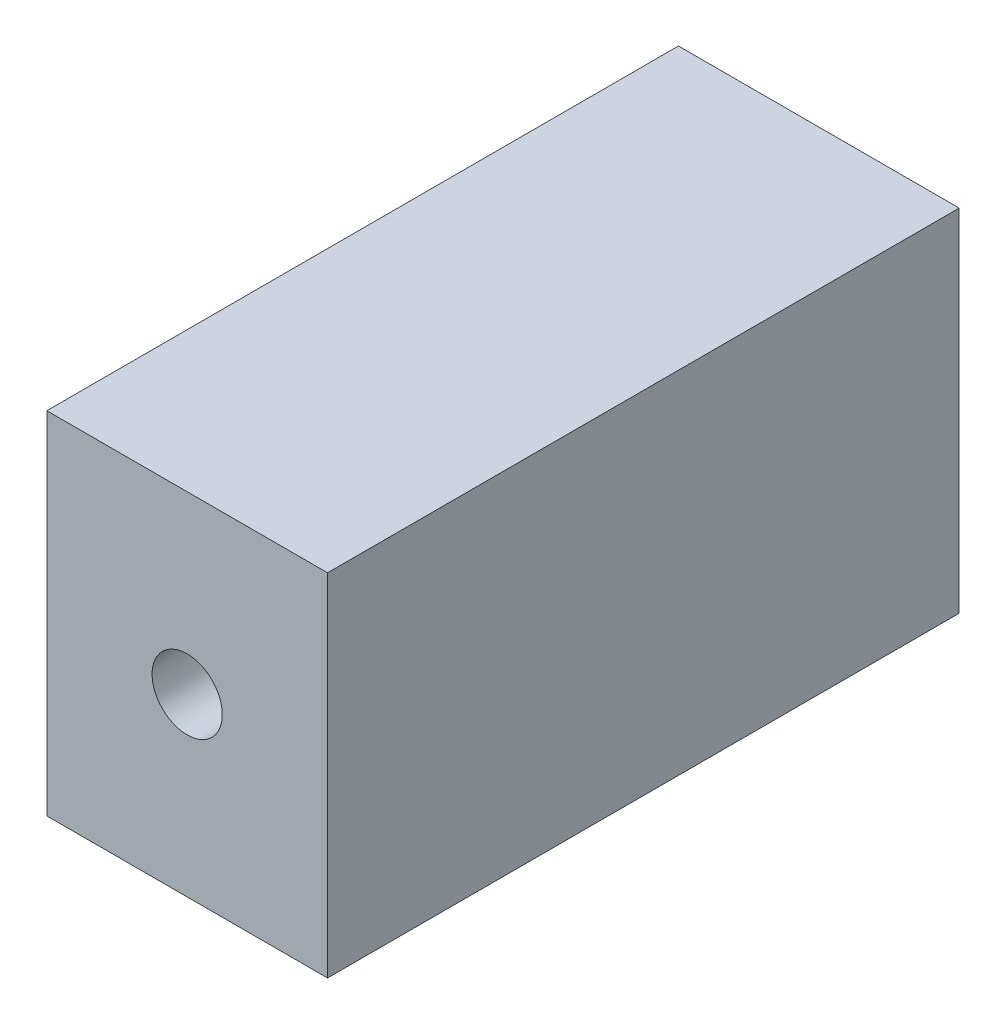
SolidWorks part; units mm, degrees
ref_plane "Front Plane" through (0, 0, 0) normal (0, 0, 1) x (1, 0, 0)
ref_plane "Top Plane" through (0, 0, 0) normal (0, 1, 0) x (1, 0, 0)
ref_plane "Right Plane" through (0, 0, 0) normal (1, 0, 0) x (0, 0, -1)
sketch "Sketch1" plane through (0, 0, 0) normal (0, 1, 0) x (1, 0, 0)
  line L1 (0, 0) -> (20.32, 0)
  line L2 (0, 0) -> (0, -45.72)
  line L3 (0, -45.72) -> (20.32, -45.72)
  line L4 (20.32, 0) -> (20.32, -45.72)
  dimension "D1" = 20.32
  dimension "D2" = 45.72
extrude "Boss-Extrude1" add sketch "Sketch1" along normal blind 25.4
sketch "Sketch2" plane through (0, 0, 45.72) normal (0, 0, 1) x (1, 0, 0)
  line L1 (0, 0) -> (20.32, 0)
  line L2 (0, 0) -> (0, 25.4)
  line L3 (0, 25.4) -> (20.32, 25.4)
  line L4 (20.32, 0) -> (20.32, 25.4)
  line L5 (0, 0) -> (20.32, 25.4) construction
  line L6 (0, 25.4) -> (20.32, 0) construction
  circle A0 centre (10.16, 12.7) radius 2.54
  point P4 (10.16, 12.7)
  dimension "D1" = 5.08
extrude "Cut-Extrude1" cut sketch "Sketch2" against normal through all contours A0
sketch "Sketch3" plane through (0, 0, 0) normal (0, -1, 0) x (-1, 0, 0)
  line L0 (-10.16, -35.56) -> (-10.16, -10.16) construction
  line L1 (0, -45.72) -> (-20.32, -45.72) construction
  line L2 (-20.32, -45.72) -> (-20.32, 0) construction
  circle A0 centre (-10.16, -35.56) radius 2.54
  circle A1 centre (-10.16, -10.16) radius 2.54
  point P4 (0, 0)
  point P7 (-10.16, -45.72)
  point P10 (-20.32, -22.86)
  point P11 (-10.16, -22.86)
  dimension "D2" = 5.08
  dimension "D1" = 25.4
extrude "Cut-Extrude2" cut sketch "Sketch3" against normal blind 7.62
